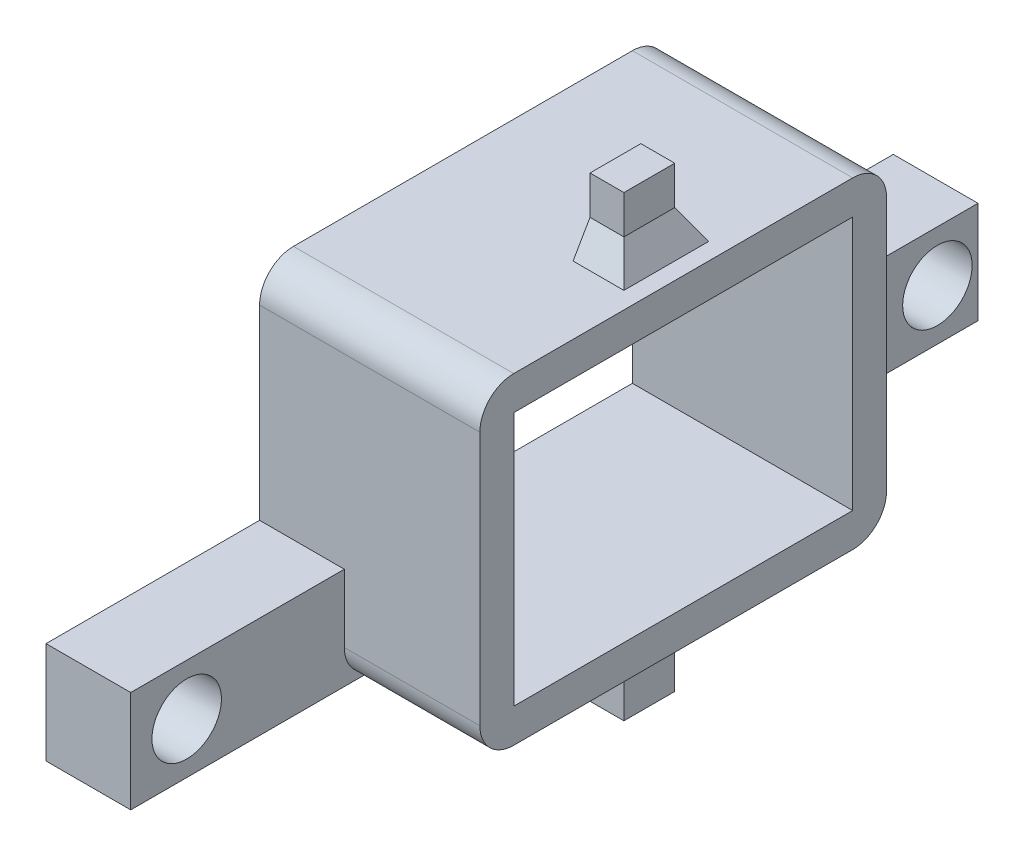
SolidWorks part; units mm, degrees
ref_plane "Front Plane" through (0, 0, 0) normal (0, 0, 1) x (1, 0, 0)
ref_plane "Top Plane" through (0, 0, 0) normal (0, 1, 0) x (1, 0, 0)
ref_plane "Right Plane" through (0, 0, 0) normal (1, 0, 0) x (0, 0, -1)
sketch "Sketch1" plane through (0, 0, 0) normal (1, 0, 0) x (0, 0, -1)
  line L1 (0, 0) -> (20, 0)
  line L2 (0, 0) -> (0, -15)
  line L3 (0, -15) -> (20, -15)
  line L4 (20, 0) -> (20, -15)
  line L5 (-2, 2) -> (22, 2)
  line L6 (-2, 2) -> (-2, -17)
  line L7 (-2, -17) -> (22, -17)
  line L8 (22, 2) -> (22, -17)
  dimension "D1" = 20
  dimension "D2" = 15
  dimension "D3" = 2
  dimension "D4" = 2
  dimension "D5" = 2
  dimension "D6" = 2
extrude "Boss-Extrude1" add sketch "Sketch1" along normal blind 13
sketch "Sketch2" plane through (0, 0, 0) normal (-1, 0, 0) x (0, 0, 1)
  line L1 (-22, -17) -> (-35.3963, -17)
  line L2 (-22, -17) -> (-22, -10.9965)
  line L3 (-22, -10.9965) -> (-35.3963, -10.9965)
  line L4 (-35.3963, -17) -> (-35.3963, -10.9965)
  line L5 (2, -17) -> (14.6037, -17)
  line L6 (2, -17) -> (2, -11)
  line L7 (2, -11) -> (14.6037, -11)
  line L8 (14.6037, -17) -> (14.6037, -11)
  circle A0 centre (-33, -13.9982) radius 2.05
  circle A1 centre (11.3, -14) radius 2.05
  point P8 (-35.3963, -13.9982)
  point P12 (14.6037, -14)
  point P13 (0, 0)
  point P14 (0, 0)
  point P20 (0, 0)
  point P21 (0, 0)
  point P22 (-36.7786, -17)
  point P23 (-35.3963, -17)
  point P24 (-32.6059, -14)
  dimension "D1" = 4.1
  dimension "D6" = 4.1
  dimension "D5" = 50
  dimension "D2" = 44.3
  dimension "D3" = 6.0035
  dimension "D4" = 6
  dimension "D7" = 13.3963
  dimension "D8" = 11
extrude "Boss-Extrude2" add sketch "Sketch2" against normal blind 5
sketch "Sketch4" plane through (0, 0, 0) normal (0, -1, 0) x (1, 0, 0)
  line L0 (13, -20) -> (0, -20) construction
  line L1 (0, 0) -> (3, 0)
  line L2 (0, 0) -> (0, -20)
  line L3 (0, -20) -> (3, -20)
  line L4 (3, 0) -> (3, -20)
  dimension "D1" = 3
extrude "Boss-Extrude3" add sketch "Sketch4" along normal blind 2
sketch "Sketch5" plane through (0, 2, 0) normal (0, 1, 0) x (1, 0, 0)
  line L1 (9, 11.5) -> (11, 11.5)
  line L2 (9, 11.5) -> (9, 8.5)
  line L3 (9, 8.5) -> (11, 8.5)
  line L4 (11, 11.5) -> (11, 8.5)
  line L6 (0, 22) -> (0, -2) construction
  point P6 (9, 10)
  dimension "D1" = 2
  dimension "D2" = 3
  dimension "D3" = 9
  dimension "D4" = 12
extrude "Boss-Extrude4" add sketch "Sketch5" along normal blind 4
sketch "Sketch6" plane through (0, -17, 0) normal (0, -1, 0) x (1, 0, 0)
  line L0 (0, 14.6037) -> (0, -35.3963) construction
  line L1 (9, -8.5) -> (11, -8.5)
  line L2 (9, -8.5) -> (9, -11.5)
  line L3 (9, -11.5) -> (11, -11.5)
  line L4 (11, -8.5) -> (11, -11.5)
  line L5 (13, 2) -> (5, 2) construction
  point P6 (11, -10)
  dimension "D1" = 2
  dimension "D2" = 3
  dimension "D3" = 9
  dimension "D4" = 12
extrude "Boss-Extrude5" add sketch "Sketch6" along normal blind 4
chamfer "Chamfer1" distance 1 angle 60 3 edges at (10, 2, -8.5) (10, 2, -11.5) (11, 2, -10)
fillet "Fillet1" radius 2 4 edges at (9, -17, -22) (9, -17, 2) (6.5, 2, -22) (6.5, 2, 2)
chamfer "Chamfer2" distance 1 angle 60 3 edges at (10, -17, -8.5) (10, -17, -11.5) (11, -17, -10)
